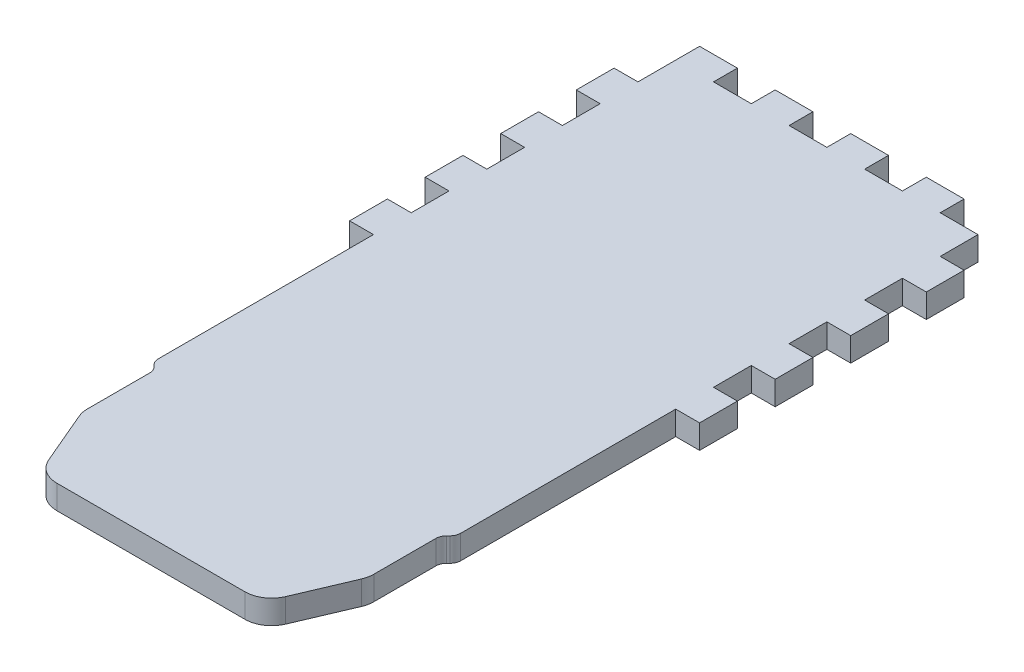
SolidWorks part; units mm, degrees
ref_plane "前视基准面" through (0, 0, 0) normal (0, 0, 1) x (1, 0, 0)
ref_plane "上视基准面" through (0, 0, 0) normal (0, 1, 0) x (1, 0, 0)
ref_plane "右视基准面" through (0, 0, 0) normal (1, 0, 0) x (0, 0, -1)
sketch "草图1" plane through (0, 0, 0) normal (0, 1, 0) x (1, 0, 0)
  line L0 (-6.2345, 62.5522) -> (0.8905, 62.5522)
  line L1 (-27.6095, 67.0522) -> (-27.6095, 55.4272)
  line L2 (-27.6095, 48.3022) -> (-27.6095, 41.1772)
  line L3 (-27.6095, 34.0522) -> (-27.6095, 26.9272)
  line L4 (-27.6095, 19.8022) -> (-27.6095, 12.6772)
  line L5 (-27.6095, 5.5522) -> (-27.6095, -34.9998)
  line L6 (29.3905, 34.0522) -> (29.3905, 26.9272)
  line L7 (29.3905, 19.8022) -> (29.3905, 12.6772)
  line L8 (29.3905, 5.5522) -> (29.3905, -34.9998)
  line L9 (0.8905, 67.0522) -> (8.0155, 67.0522)
  line L10 (-16.8417, -64.8978) -> (18.6226, -64.8978)
  line L11 (-25.7097, -51.8366) -> (-21.4418, -61.857)
  line L12 (-26.1095, -38.1567) -> (-26.1095, -49.8773)
  line L13 (27.4906, -51.8366) -> (23.2228, -61.857)
  line L14 (27.8905, -38.1567) -> (27.8905, -49.8773)
  line L15 (28.4763, -36.7424) -> (28.8047, -36.414)
  line L16 (-26.6953, -36.7424) -> (-27.0237, -36.414)
  line L17 (0.8905, 62.5522) -> (0.8905, 67.0522)
  line L18 (-13.3595, 62.5522) -> (-13.3595, 67.0522)
  line L19 (-20.4845, 67.0522) -> (-27.6095, 67.0522)
  line L20 (15.1405, 67.0522) -> (15.1405, 62.5522)
  line L21 (22.2655, 62.5522) -> (29.3905, 62.5522)
  line L22 (-20.4845, 67.0522) -> (-20.4845, 62.5522)
  line L23 (-20.4845, 62.5522) -> (-13.3595, 62.5522)
  line L24 (-13.3595, 67.0522) -> (-6.2345, 67.0522)
  line L25 (15.1405, 67.0522) -> (22.2655, 67.0522)
  line L26 (8.0155, 62.5522) -> (15.1405, 62.5522)
  line L27 (-6.2345, 67.0522) -> (-6.2345, 62.5522)
  line L28 (22.2655, 67.0522) -> (22.2655, 62.5522)
  line L29 (8.0155, 67.0522) -> (8.0155, 62.5522)
  line L30 (-32.1095, 5.5522) -> (-32.1095, 12.6772)
  line L31 (-32.1095, 19.8022) -> (-32.1095, 26.9272)
  line L32 (-32.1095, 34.0522) -> (-32.1095, 41.1772)
  line L33 (-32.1095, 48.3022) -> (-32.1095, 55.4272)
  line L34 (-32.1095, 5.5522) -> (-27.6095, 5.5522)
  line L35 (-32.1095, 34.0522) -> (-27.6095, 34.0522)
  line L36 (-27.6095, 48.3022) -> (-32.1095, 48.3022)
  line L37 (-32.1095, 41.1772) -> (-27.6095, 41.1772)
  line L38 (-32.1095, 55.4272) -> (-27.6095, 55.4272)
  line L39 (-27.6095, 19.8022) -> (-32.1095, 19.8022)
  line L40 (-32.1095, 26.9272) -> (-27.6095, 26.9272)
  line L41 (-32.1095, 12.6772) -> (-27.6095, 12.6772)
  line L42 (29.3905, 62.5522) -> (29.3905, 55.4272)
  line L43 (29.3905, 48.3022) -> (29.3905, 41.1772)
  line L44 (33.8905, 5.5522) -> (33.8905, 12.6772)
  line L45 (33.8905, 19.8022) -> (33.8905, 26.9272)
  line L46 (33.8905, 34.0522) -> (33.8905, 41.1772)
  line L47 (33.8905, 48.3022) -> (33.8905, 55.4272)
  line L48 (33.8905, 34.0522) -> (29.3905, 34.0522)
  line L49 (29.3905, 48.3022) -> (33.8905, 48.3022)
  line L50 (33.8905, 41.1772) -> (29.3905, 41.1772)
  line L51 (33.8905, 55.4272) -> (29.3905, 55.4272)
  line L52 (29.3905, 19.8022) -> (33.8905, 19.8022)
  line L53 (33.8905, 26.9272) -> (29.3905, 26.9272)
  line L54 (33.8905, 12.6772) -> (29.3905, 12.6772)
  line L55 (33.8905, 5.5522) -> (29.3905, 5.5522)
  circle A0 centre (0, 0) radius 5
  circle A1 centre (0, 0) radius 2
  arc A2 (-21.4418, -61.857) -> (-16.8417, -64.8978) centre (-16.8417, -59.8978) ccw
  arc A3 (-26.1095, -49.8773) -> (-25.7097, -51.8366) centre (-21.1095, -49.8773) ccw
  arc A4 (18.6226, -64.8978) -> (23.2228, -61.857) centre (18.6226, -59.8978) ccw
  arc A5 (-26.1095, -38.1567) -> (-26.6953, -36.7424) centre (-28.1095, -38.1567) ccw
  arc A6 (27.4906, -51.8366) -> (27.8905, -49.8773) centre (22.8905, -49.8773) ccw
  arc A7 (28.4763, -36.7424) -> (27.8905, -38.1567) centre (29.8905, -38.1567) ccw
  arc A8 (28.8047, -36.414) -> (29.3905, -34.9998) centre (27.3905, -34.9998) ccw
  arc A9 (-27.6095, -34.9998) -> (-27.0237, -36.414) centre (-25.6095, -34.9998) ccw
extrude "凸台-拉伸1" add sketch "草图1" along normal blind 4.5 contours L5 A9 L16 A5 L12 A3 L11 A2 L10 A4 L13 A6 L14 A7 L15 A8 L8 L55 L44 L54 L7 L52 L45 L53 L6 L48 L46 L50 L43 L49 L47 L51 L42 L21 L28 L25 L20 L26 L29 L9 L17 L0 L27 L24 L18 L23 L22 L19 L1 L38 L33 L36 L2 L37 L32 L35 L3 L40 L31 L39 L4 L41 L30 L34
